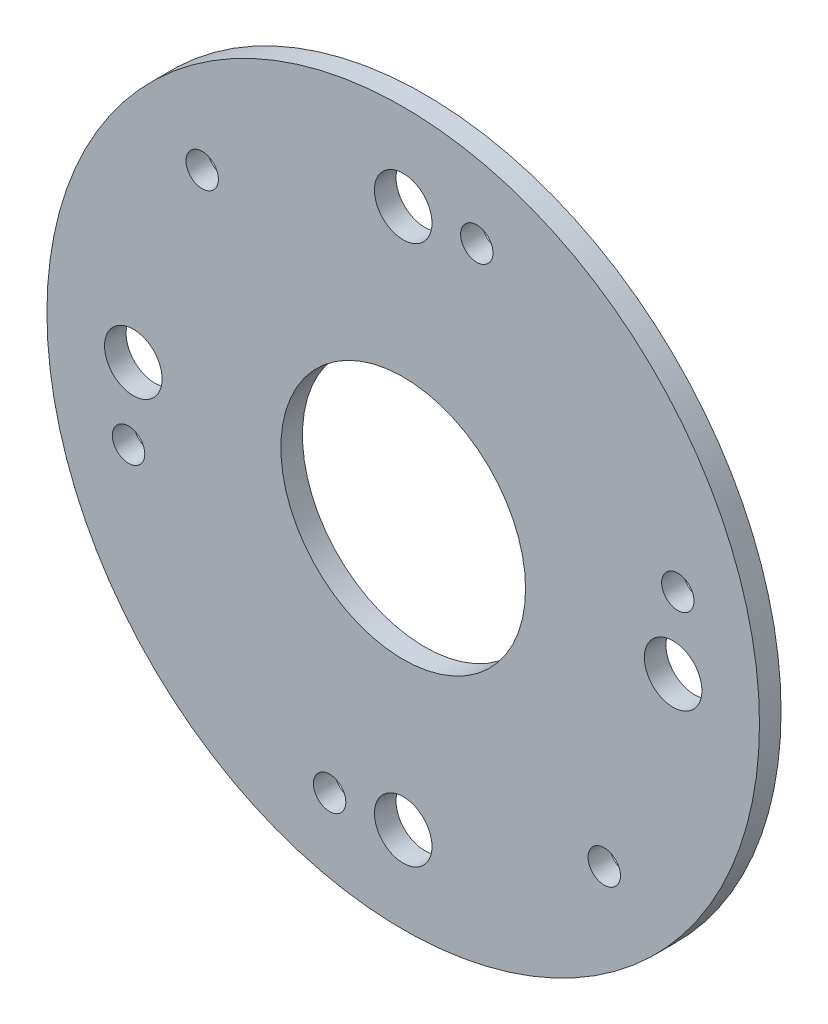
SolidWorks part; units mm, degrees
ref_plane "Спереди" through (0, 0, 0) normal (0, 0, 1) x (1, 0, 0)
ref_plane "Сверху" through (0, 0, 0) normal (0, 1, 0) x (1, 0, 0)
ref_plane "Справа" through (0, 0, 0) normal (1, 0, 0) x (0, 0, -1)
sketch "Эскиз1" plane through (0, 0, 0) normal (0, 0, 1) x (1, 0, 0)
  circle A0 centre (0, 0) radius 49.5
  circle A1 centre (0, 0) radius 17
extrude "Carrier_front" add sketch "Эскиз1" along normal blind 3 from offset 55.5
sketch "Эскиз2" plane through (0, 0, 0) normal (0, 0, 1) x (1, 0, 0)
  circle A0 centre (37.5, 0) radius 2.25
  circle A1 centre (0, 37.5) radius 2.25
  circle A2 centre (-37.5, 0) radius 2.25
  circle A3 centre (0, -37.5) radius 2.25
  circle A4 centre (38.1541, 10.2234) radius 2.25
  circle A5 centre (10.2234, 38.1541) radius 2.25
  circle A6 centre (-27.9307, 27.9307) radius 2.25
  circle A7 centre (-38.1541, -10.2234) radius 2.25
  circle A8 centre (-10.2234, -38.1541) radius 2.25
  circle A9 centre (27.9307, -27.9307) radius 2.25
extrude "Through_holes" cut sketch "Эскиз2" against normal mid plane 200
sketch "Эскиз3" plane through (0, 0, 0) normal (0, 0, 1) x (1, 0, 0)
  circle A0 centre (37.5, 0) radius 4
  circle A1 centre (0, 37.5) radius 4
  circle A2 centre (-37.5, 0) radius 4
  circle A3 centre (0, -37.5) radius 4
extrude "Вырез-Вытянуть2" cut sketch "Эскиз3" against normal mid plane 200
